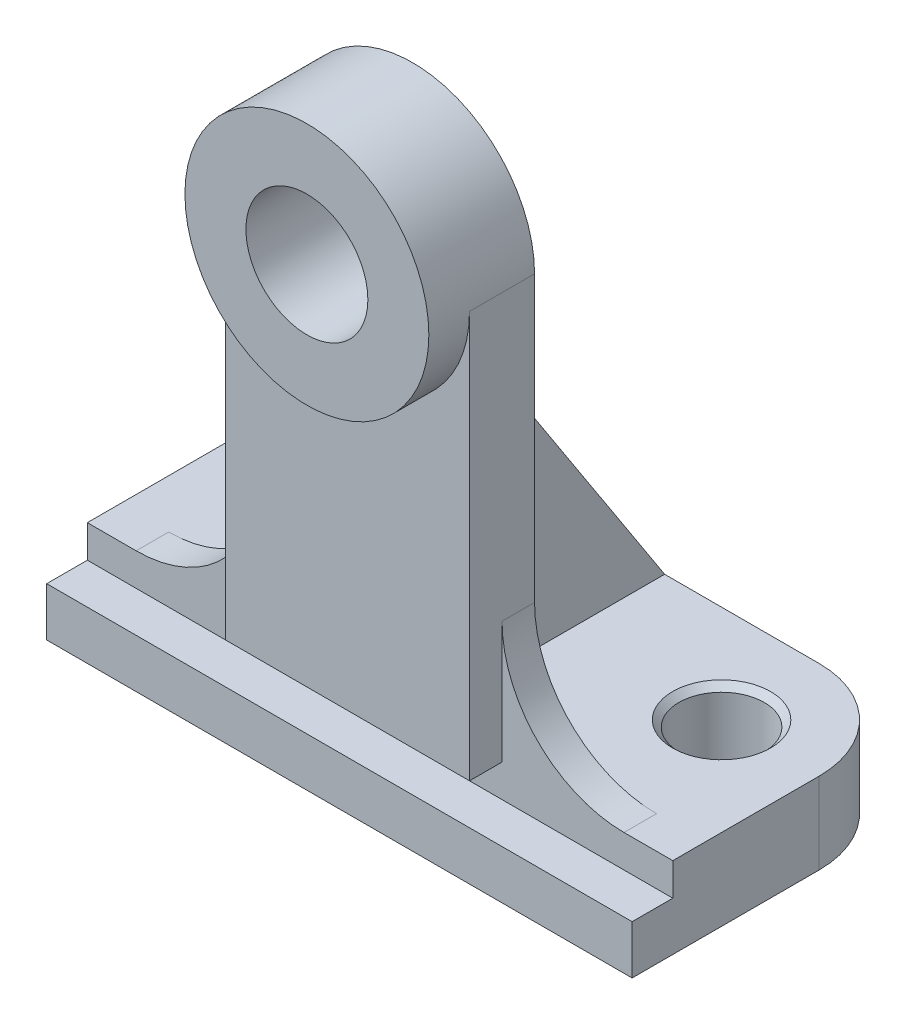
SolidWorks part; units mm, degrees
material "Ductile Iron"
ref_plane "Front Plane" through (0, 0, 0) normal (0, 0, 1) x (1, 0, 0)
ref_plane "Top Plane" through (0, 0, 0) normal (0, 1, 0) x (1, 0, 0)
ref_plane "Right Plane" through (0, 0, 0) normal (1, 0, 0) x (0, 0, -1)
sketch "Sketch1" plane through (0, 0, 0) normal (1, 0, 0) x (0, 0, -1)
  line L1 (-17.5, -5) -> (17.5, -5)
  line L2 (-17.5, -5) -> (-17.5, 5)
  line L3 (-17.5, 5) -> (17.5, 5)
  line L4 (17.5, -5) -> (17.5, 5)
  line L5 (-17.5, -5) -> (17.5, 5) construction
  line L6 (-17.5, 5) -> (17.5, -5) construction
  line L7 (-17.5, 5) -> (-12.5, 5)
  line L8 (-17.5, 5) -> (-17.5, 1)
  line L9 (-17.5, 1) -> (-12.5, 1)
  line L10 (-12.5, 5) -> (-12.5, 1)
  point P0 (0, 0)
  dimension "D1" = 10
  dimension "D2" = 35
  dimension "D3" = 5
  dimension "D4" = 4
extrude "Boss-Extrude1" add sketch "Sketch1" along normal mid plane 72 contours L3 L10 L9 L2 L1 L4
sketch "Sketch2" plane through (0, 0, 12.5) normal (0, 0, 1) x (1, 0, 0)
  line L0 (0, -26.3304) -> (0, 26.3304) construction
  line L2 (-15, 55) -> (15, 55)
  line L3 (-15, 55) -> (-15, 5)
  line L4 (-15, 5) -> (15, 5)
  line L5 (15, 55) -> (15, 5)
  line L6 (-15, 55) -> (15, 5) construction
  line L7 (-15, 5) -> (15, 55) construction
  line L9 (36, 5) -> (-36, 5) construction
  arc A0 (-15, 55) -> (15, 55) centre (0, 55) cw
  circle A1 centre (0, 55) radius 7.5
  point P0 (0, 30)
  point P4 (0, 0)
  line M7 (36, 5) -> (-36, 5)
  dimension "D3" = 15
  dimension "D1" = 50
  dimension "D2" = 30
extrude "Boss-Extrude2" add sketch "Sketch2" along normal mid plane 8 contours A1 L2 L3 L5 M7 | A1 L2 A0
sketch "Sketch3" plane through (0, 0, 16.5) normal (0, 0, 1) x (1, 0, 0)
  circle A0 centre (0, 55) radius 15
  arc A1 (15, 55) -> (-15, 55) centre (0, 55) ccw construction
  circle A4 centre (0, 55) radius 7.5
  circle A5 centre (0, 55) radius 7.5
  dimension "D1" = 0
extrude "Boss-Extrude3" add sketch "Sketch3" along normal blind 5
fillet "Fillet2" radius 15 2 edges at (-15, 5, 10.5) (15, 5, 10.5)
sketch "Sketch4" plane through (0, 0, 0) normal (1, 0, 0) x (0, 0, -1)
  line L0 (17.5, 5) -> (-8.5, 45)
  line L1 (-8.5, 55) -> (-8.5, 20) construction
  line L2 (-12.5, 5) -> (17.5, 5) construction
  dimension "D1" = 40
rib "Rib1" sketch "Sketch4" sketch "Sketch4" thickness 10 extrusion direction parallel to sketch draft on no parameters "D1"=10
fillet "Fillet3" radius 12 2 edges at (-36, 0, -17.5) (36, 0, -17.5)
hole_wizard "M12x1.5 Tapped Hole1" positions "Sketch5" profile "Sketch6" tap size "M12x1.5" standard "ISO" end condition through all
sketch "Sketch5" plane through (0, 5, 0) normal (0, 1, 0) x (1, 0, 0)
  point P0 (24, 5.5)
  point P3 (-24, 5.5)
sketch "Sketch6" plane through (24, 5, -5.5) normal (1, 0, 0) x (0, 0, 1)
  line L0 (0, 0) -> (0, 10)
  line L1 (0, 10) -> (5.25, 10)
  line L2 (5.25, 10) -> (5.25, 0.775)
  line L3 (5.25, 0.775) -> (6.025, 0)
  line L5 (6.025, 0) -> (0, 0)
  line L6 (-5.25, 0.775) -> (-6.025, 0) construction
  line L11 (0, -6.35) -> (0, 107.95) construction
  dimension "Thru Tap Drill Dia." = 10.5
  dimension "Thru Tap Drill Depth" = 10
  dimension "Near C'Sink Dia." = 12.05
  dimension "Near C'Sink Angle" = 90
cosmetic thread "Hole Thread1" parameters "D2"=12
cosmetic thread "Hole Thread2" parameters "D2"=12
